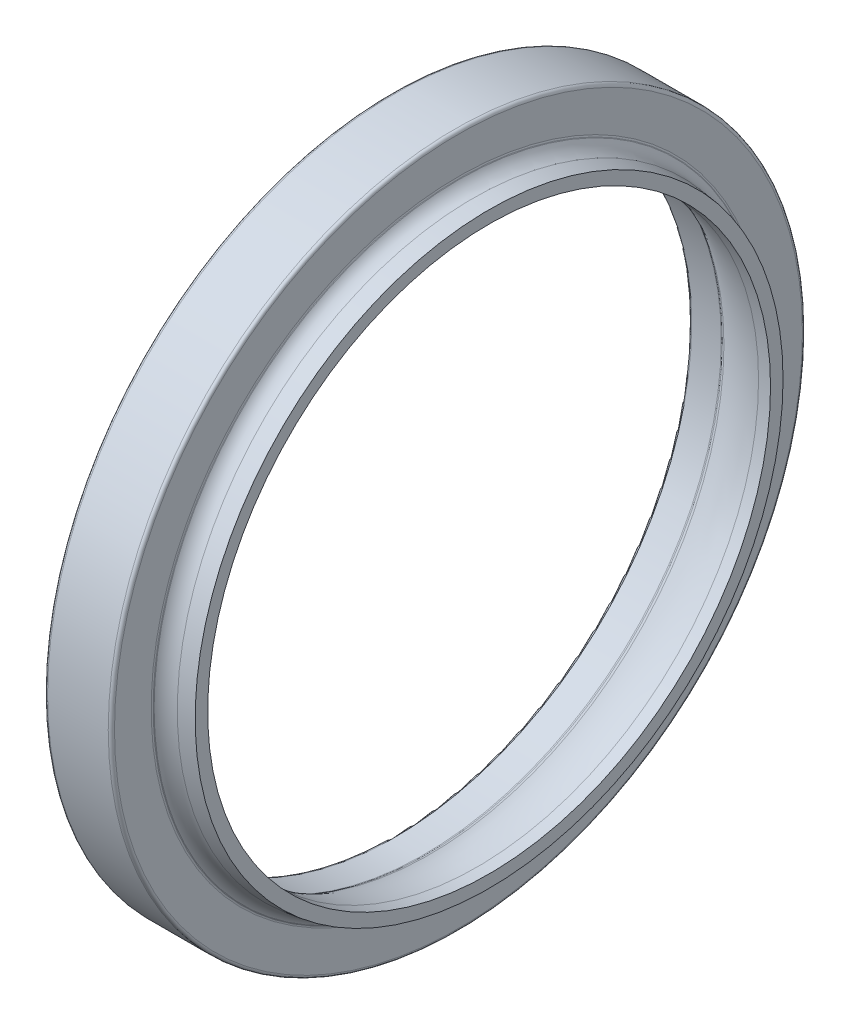
SolidWorks part; units mm, degrees
ref_plane "Front Plane" through (0, 0, 0) normal (0, 0, 1) x (1, 0, 0)
ref_plane "Top Plane" through (0, 0, 0) normal (0, 1, 0) x (1, 0, 0)
ref_plane "Right Plane" through (0, 0, 0) normal (1, 0, 0) x (0, 0, -1)
ref_axis "Axis1" through (88.99, 0, 0) along (-1, 0, 0)
sketch "Sketch1" plane through (0, 0, 0) normal (0, 1, 0) x (1, 0, 0)
  line L0 (0, 0) -> (0, 23.75) construction
  line L1 (7.8, 23.5) -> (7.8, 22.5)
  line L2 (0, 23.75) -> (5.35, 23.75) construction
  line L3 (0, 24) -> (0, 27.5)
  line L4 (0.25, 27.75) -> (5.1, 27.75)
  line L5 (5.35, 23.75) -> (5.35, 27.75) construction
  line L6 (7.8, 22.5) -> (6.8423, 22.5)
  line L7 (3.0397, 23.5355) -> (2.7337, 23.7155)
  line L8 (5.3835, 24.442) -> (5.4105, 24.3952)
  line L9 (6.5268, 23.6563) -> (7.8, 23.5)
  line L10 (0.25, 23.75) -> (2.6069, 23.75)
  line L11 (5.35, 24.567) -> (5.35, 27.5)
  arc A0 (5.4105, 24.3952) -> (6.5268, 23.6563) centre (6.7096, 25.1452) ccw
  arc A1 (6.8423, 22.5) -> (3.0397, 23.5355) centre (6.8423, 30) cw
  arc A2 (5.3835, 24.442) -> (5.35, 24.567) centre (5.6, 24.567) cw
  arc A3 (5.1, 27.75) -> (5.35, 27.5) centre (5.1, 27.5) cw
  arc A4 (0, 27.5) -> (0.25, 27.75) centre (0.25, 27.5) cw
  arc A5 (0, 24) -> (0.25, 23.75) centre (0.25, 24) ccw
  arc A6 (2.7337, 23.7155) -> (2.6069, 23.75) centre (2.6069, 23.5) ccw
  point P16 (4.8, 22.5)
  point P19 (5.35, 24.5)
  point P25 (0, 27.75)
  point P31 (2.675, 23.75)
  dimension "D11" = 1.5
  dimension "D12" = 7.5
  dimension "D13" = 0.25
  dimension "D1" = 23.75
  dimension "D2" = 4
  dimension "D3" = 5.35
  dimension "D4" = 1
  dimension "D5" = 1.25
  dimension "D6" = 3
  dimension "D7" = 2.45
  dimension "D8" = 0.75
  dimension "D9" = 30
  dimension "D10" = 97
revolve "Revolve1" add sketch "Sketch1" angle 360 about axis through (88.99, 0, 0) along (-1, 0, 0)
